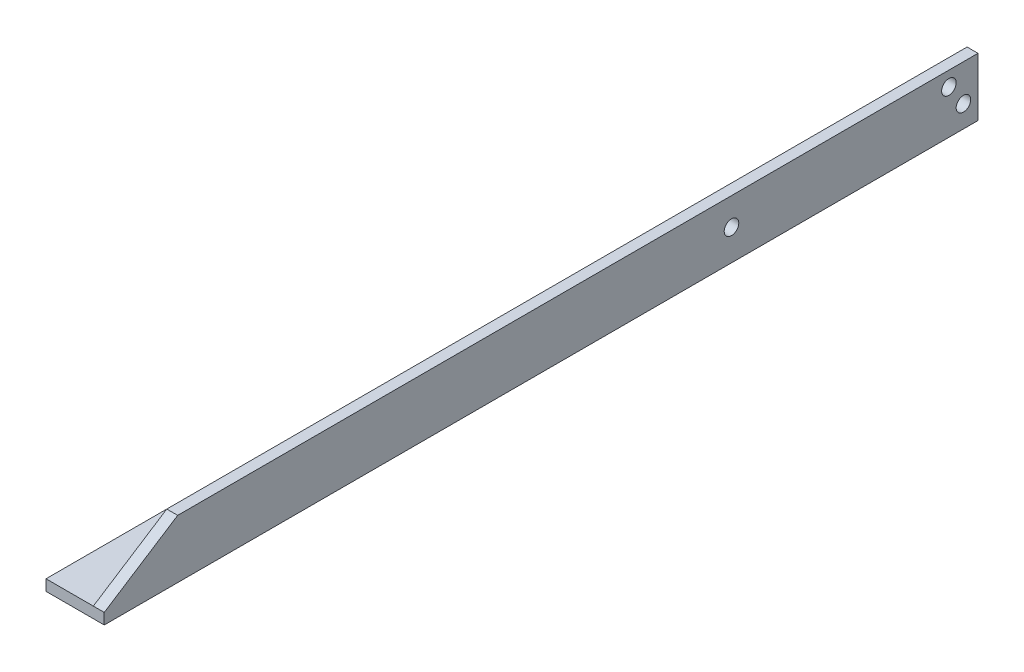
SolidWorks part; units mm, degrees
material "6061 Alloy"
ref_plane "Front Plane" through (0, 0, 0) normal (0, 0, 1) x (1, 0, 0)
ref_plane "Top Plane" through (0, 0, 0) normal (0, 1, 0) x (1, 0, 0)
ref_plane "Right Plane" through (0, 0, 0) normal (1, 0, 0) x (0, 0, -1)
sketch "Sketch1" plane through (0, 0, 0) normal (0, 0, 1) x (1, 0, 0)
  line L0 (0, 0) -> (0, -25.4)
  line L1 (0, -25.4) -> (-25.4, -25.4)
  line L2 (-4.7625, 0) -> (-4.7625, -20.6375)
  line L3 (-4.7625, -20.6375) -> (-25.4, -20.6375)
  line L4 (-4.7625, 0) -> (0, 0)
  line L5 (-25.4, -25.4) -> (-25.4, -20.6375)
  dimension "D1" = 25.4
  dimension "D2" = 25.4
  dimension "D3" = 4.7625
extrude "Boss-Extrude1" add sketch "Sketch1" along normal blind 381
sketch "Sketch4" plane through (-4.7625, 0, 0) normal (-1, 0, 0) x (0, 0, 1)
  line L0 (381, -20.6375) -> (348.9734, 0)
  line L1 (381, 0) -> (0, 0) construction
  dimension "D1" = 38.1
extrude "Cut-Extrude3" cut sketch "Sketch4" against normal through all and the other way through all flip side to cut
sketch "Sketch6" plane through (-4.7625, 0, 0) normal (-1, 0, 0) x (0, 0, 1)
  line L0 (348.9734, 0) -> (0, 0) construction
  line L1 (0, 0) -> (0, -20.6375) construction
  circle A0 centre (6.35, -15.875) radius 3.175
  circle A1 centre (12.7, -6.35) radius 3.175
  dimension "D1" = 6.35
  dimension "D2" = 6.35
  dimension "D3" = 6.35
  dimension "D4" = 6.35
  dimension "D5" = 12.7
  dimension "D6" = 15.875
extrude "Cut-Extrude4" cut sketch "Sketch6" against normal up to next
sketch "Sketch7" plane through (0, 0, 0) normal (1, 0, 0) x (0, 0, -1)
  circle A0 centre (-107.4907, -11.9296) radius 3.175 construction
  circle A1 centre (-107.4907, -11.9296) radius 3.175
extrude "Cut-Extrude5" cut sketch "Sketch7" against normal up to next
sketch "Sketch8" plane through (0, -20.6375, 0) normal (0, 1, 0) x (1, 0, 0)
  line L0 (-25.4, -381) -> (-25.4, 0) construction
  line L1 (-4.7625, 0) -> (-25.4, 0) construction
  circle A0 centre (-15.0812, -12.7) radius 3.175
  dimension "D1" = 6.35
  dimension "D2" = 10.3187
  dimension "D3" = 12.7
extrude "Cut-Extrude6" cut sketch "Sketch8" against normal up to next
equation "\"1..500in\"=1"
